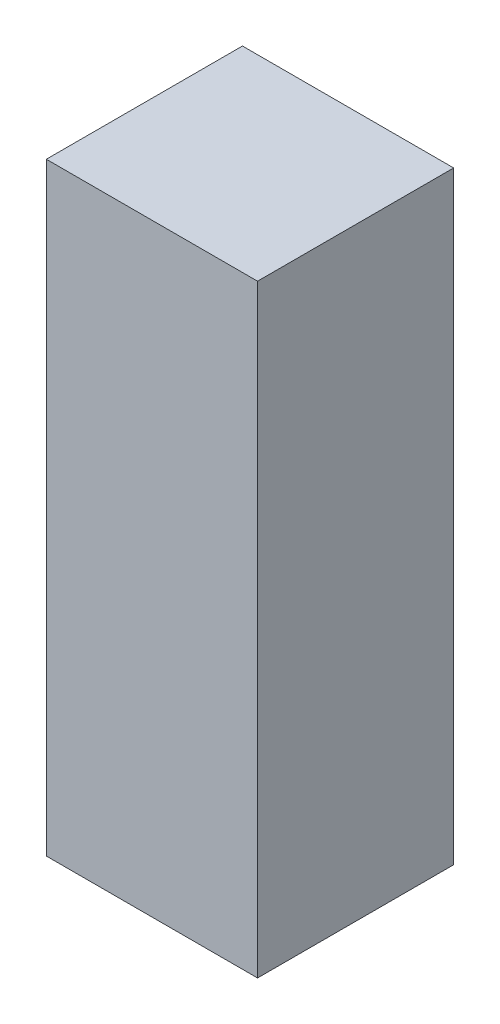
SolidWorks part; units mm, degrees
ref_plane "Front Plane" through (0, 0, 0) normal (0, 0, 1) x (1, 0, 0)
ref_plane "Top Plane" through (0, 0, 0) normal (0, 1, 0) x (1, 0, 0)
ref_plane "Right Plane" through (0, 0, 0) normal (1, 0, 0) x (0, 0, -1)
other "Configuration Table"
sketch "Sketch1" plane through (0, 0, 0) normal (0, 0, 1) x (1, 0, 0)
  line L1 (24, 1870) -> (38, 1870)
  line L2 (24, 1870) -> (24, 1910)
  line L3 (24, 1910) -> (38, 1910)
  line L4 (38, 1870) -> (38, 1910)
extrude "PACK_sarjor_kapisi_mentese_2_1" add sketch "Sketch1" along normal blind 13 from offset 20 separate body
